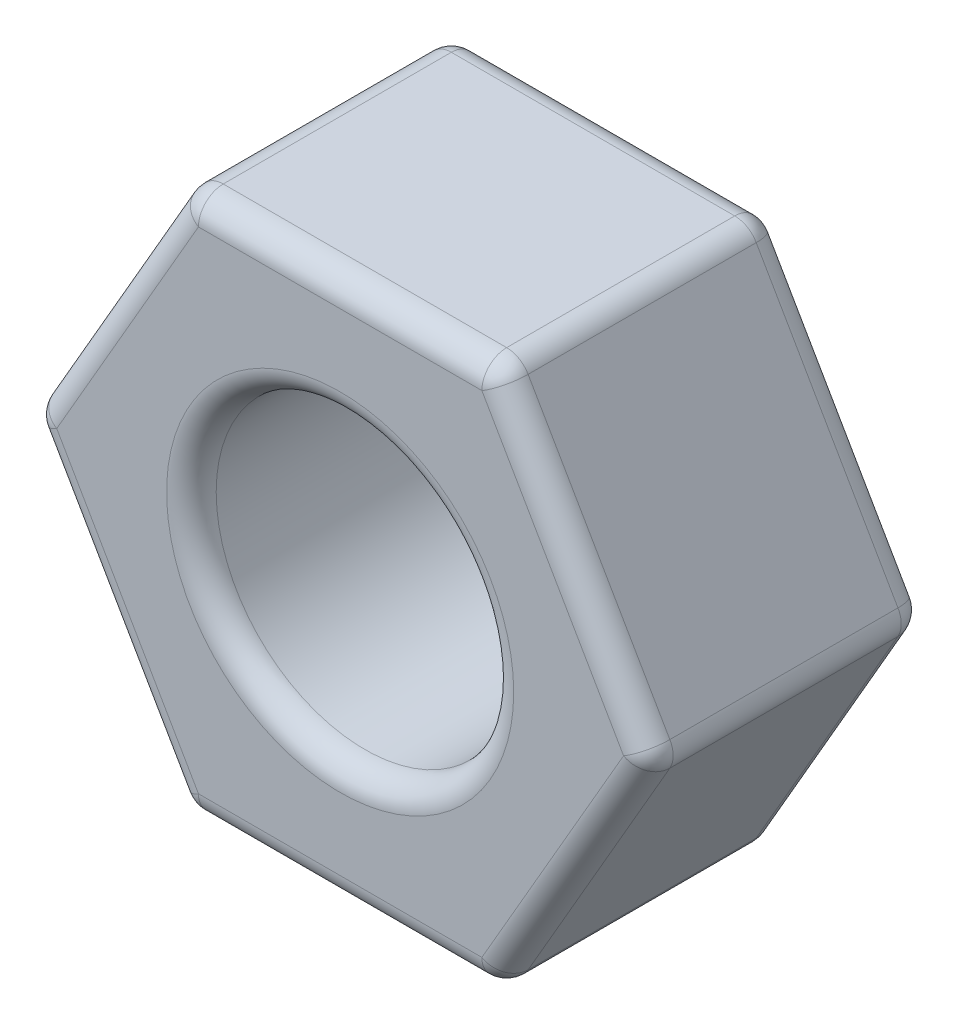
SolidWorks part; units mm, degrees
ref_plane "Plano frontal" through (0, 0, 0) normal (0, 0, 1) x (1, 0, 0)
ref_plane "Plano superior" through (0, 0, 0) normal (0, 1, 0) x (1, 0, 0)
ref_plane "Plano direito" through (0, 0, 0) normal (1, 0, 0) x (0, 0, -1)
sketch "Esboço1" plane through (0, 0, 0) normal (0, 0, 1) x (1, 0, 0)
  line L1 (-6.2931, 0) -> (-3.1466, -5.45)
  line L2 (-3.1466, -5.45) -> (3.1466, -5.45)
  line L3 (3.1466, -5.45) -> (6.2931, 0)
  line L4 (6.2931, 0) -> (3.1466, 5.45)
  line L5 (3.1466, 5.45) -> (-3.1466, 5.45)
  line L6 (-3.1466, 5.45) -> (-6.2931, 0)
  circle A0 centre (0, 0) radius 3
  circle A1 centre (0, 0) radius 5.45 construction
  dimension "D1" = 6
  dimension "D2" = 10.9
extrude "Ressalto-extrusão2" add sketch "Esboço1" along normal blind 5.6
fillet "Filete1" radius 0.5 20 edges at (3, 0, 5.6) (-4.7198, 2.725, 5.6) (-6.2931, 0, 2.8) (-3.1466, -5.45, 2.8) (0, -5.45, 5.6) (3.1466, -5.45, 2.8) (4.7198, -2.725, 5.6) (6.2931, 0, 2.8) (4.7198, 2.725, 5.6) (3.1466, 5.45, 2.8) (0, 5.45, 5.6) (-3.1466, 5.45, 2.8) (3, 0, 0) (-4.7198, -2.725, 0) (0, -5.45, 0) (4.7198, -2.725, 0) (4.7198, 2.725, 0) (0, 5.45, 0) (-4.7198, 2.725, 0) (-4.7198, -2.725, 5.6)
